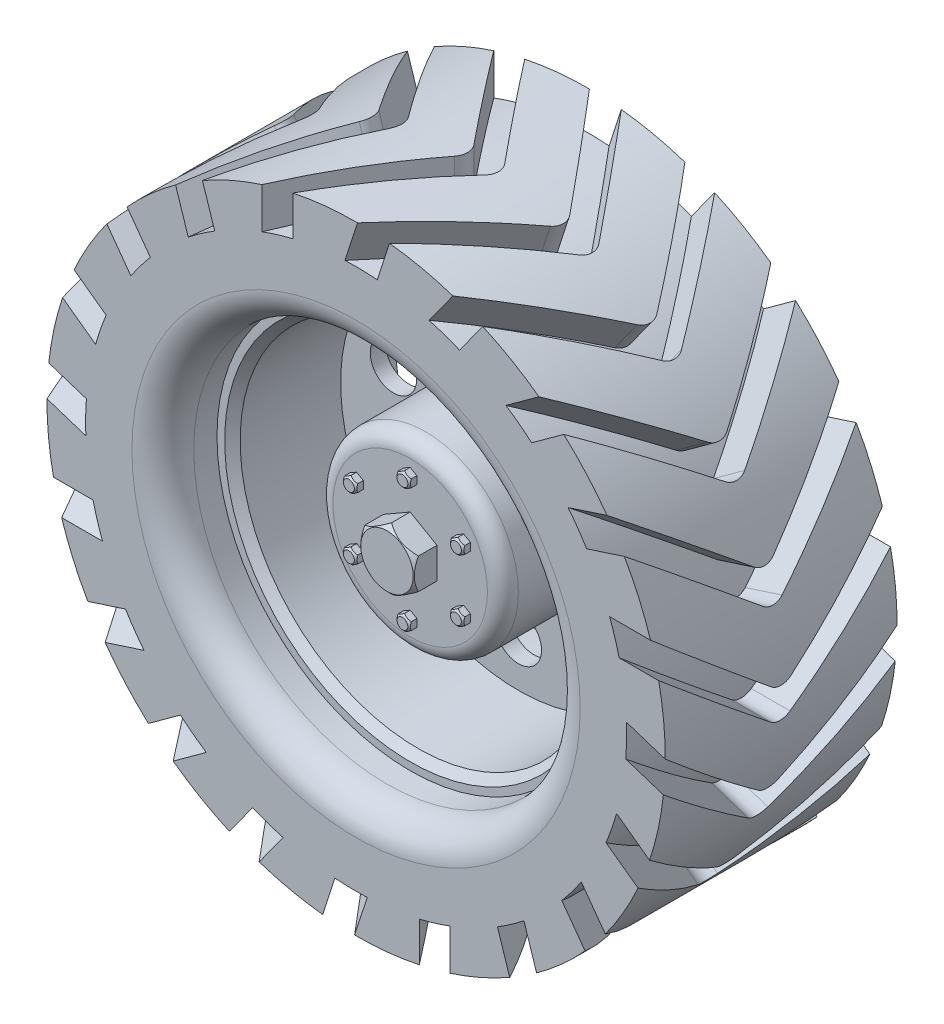
SolidWorks part; units mm, degrees
ref_plane "前基準面" through (0, 0, 0) normal (0, 0, 1) x (1, 0, 0)
ref_plane "上基準面" through (0, 0, 0) normal (0, 1, 0) x (1, 0, 0)
ref_plane "右基準面" through (0, 0, 0) normal (1, 0, 0) x (0, 0, -1)
sketch "草圖1" plane through (0, 0, 0) normal (0, 0, 1) x (1, 0, 0)
  circle A0 centre (0, 0) radius 125
  dimension "D1" = 250
extrude "填料-伸長1" add sketch "草圖1" along normal mid plane 80
shell "薄殼1" thickness 10
sketch "草圖3" plane through (0, 0, 0) normal (0, 0, 1) x (1, 0, 0)
  circle A0 centre (0, 0) radius 200
  circle A1 centre (0, 0) radius 125
  dimension "D1" = 400
  dimension "D2" = 250
extrude "填料-伸長2" add sketch "草圖3" along normal mid plane 150
chamfer "導角1" distance 5 angle 45 1 edges at (115, 0, 40)
fillet "圓角2" radius 20 1 edges at (125, 0, 75)
sketch "草圖4" plane through (0, 0, -30) normal (0, 0, 1) x (1, 0, 0)
  circle A0 centre (0, 0) radius 60
  dimension "D1" = 120
extrude "填料-伸長3" add sketch "草圖4" along normal up to surface (70 mm away) up to face at (120, 0, 40)
fillet "圓角4" radius 10 1 edges at (60, 0, 40)
sketch "草圖5" plane through (0, 0, -30) normal (0, 0, 1) x (1, 0, 0)
  line L0 (0, 0) -> (0, 85) construction
  circle A0 centre (0, 85) radius 15
  dimension "D1" = 30
  dimension "D2" = 85
extrude "除料-伸長2" cut sketch "草圖5" against normal blind 100
pattern_circular "環狀複製排列1" count 10 over 360 about axis through (0, 0, 0) along (0, 0, 1) of "除料-伸長2"
fillet "圓角5" radius 5 1 edges at (60, 0, -30)
sketch "草圖7" plane through (0, 0, 40) normal (0, 0, 1) x (1, 0, 0)
  circle A0 centre (0, 0) radius 20
  dimension "D1" = 40
extrude "填料-伸長5" add sketch "草圖7" along normal blind 15
chamfer "導角2" distance 3 angle 45 1 edges at (20, 0, 55)
sketch "草圖8" plane through (0, 0, 55) normal (0, 0, 1) x (1, 0, 0)
  line L1 (0, 20) -> (-17.3205, 10)
  line L2 (-17.3205, 10) -> (-17.3205, -10)
  line L3 (-17.3205, -10) -> (0, -20)
  line L4 (0, -20) -> (17.3205, -10)
  line L5 (17.3205, -10) -> (17.3205, 10)
  line L6 (17.3205, 10) -> (0, 20)
  circle A0 centre (0, 0) radius 17.3205 construction
  circle A1 centre (0, 0) radius 20
extrude "除料-伸長3" cut sketch "草圖8" against normal blind 15 contours L1 A1 | L6 A1 | L2 A1 | L3 A1 | L4 A1 | L5 A1
sketch "草圖9" plane through (0, 0, 40) normal (0, 0, 1) x (1, 0, 0)
  circle A0 centre (0, 0) radius 40 construction
  circle A1 centre (0, 40) radius 5
  dimension "D1" = 80
  dimension "D2" = 10
extrude "填料-伸長6" add sketch "草圖9" along normal blind 5
chamfer "導角3" distance 1.5 angle 45 1 edges at (5, 40, 45)
pattern_circular "環狀複製排列2" count 6 over 360 about axis through (0, 0, 0) along (0, 0, 1) of "填料-伸長6"
chamfer "導角4" distance 1.5 angle 45 5 edges at (37.141, 15.6699, 45) (32.141, -24.3301, 45) (-5, -40, 45) (-37.141, -15.6699, 45) (-32.141, 24.3301, 45)
sketch "草圖10" plane through (0, 0, 45) normal (0, 0, 1) x (1, 0, 0)
  line L1 (0, 45) -> (-4.3301, 42.5)
  line L2 (-4.3301, 42.5) -> (-4.3301, 37.5)
  line L3 (-4.3301, 37.5) -> (0, 35)
  line L4 (0, 35) -> (4.3301, 37.5)
  line L5 (4.3301, 37.5) -> (4.3301, 42.5)
  line L6 (4.3301, 42.5) -> (0, 45)
  circle A0 centre (0, 40) radius 4.3301 construction
  circle A1 centre (0, 40) radius 5
extrude "除料-伸長4" cut sketch "草圖10" against normal blind 5 contours L1 A1 | L6 A1 | L2 A1 | L3 A1 | L4 A1 | L5 A1
pattern_circular "環狀複製排列4" count 6 over 360 about axis through (0, 0, 0) along (0, 0, 1) of "除料-伸長4"
ref_plane "平面1" through (0, 300, 0) normal (0, 1, 0) x (1, 0, 0)
sketch "草圖11" plane through (0, 300, 0) normal (0, 1, 0) x (1, 0, 0)
  line L1 (-5.1172, -6.303) -> (-60.8905, -75)
  line L2 (0, 0) -> (20, 0) construction
  line L8 (-200, -75) -> (200, -75) construction
  line L9 (-5.1172, 6.303) -> (-60.8905, 75)
  line L10 (200, 75) -> (-200, 75) construction
  line L11 (-60.8905, 75) -> (-60.8905, -75) construction
  line L16 (14.8828, -6.303) -> (-40.8905, -75)
  line L17 (14.8828, 6.303) -> (-40.8905, 75)
  line L18 (-60.8905, -75) -> (-40.8905, -75)
  line L19 (-60.8905, 75) -> (-40.8905, 75)
  arc A0 (14.8828, -6.303) -> (14.8828, 6.303) centre (7.1192, 0) ccw
  arc A1 (-5.1172, -6.303) -> (-5.1172, 6.303) centre (-12.8808, 0) ccw
  dimension "D2" = 10
  dimension "D1" = 20
sketch "草圖13" plane through (0, 0, 75) normal (0, 0, 1) x (1, 0, 0)
  circle A0 centre (0, 0) radius 175
  dimension "D1" = 350
surface "曲面-伸長1" sketch "草圖13" parameters "D1"=176
extrude "除料-伸長5" cut sketch "草圖11" against normal up to surface (125.0748 mm away)
pattern_circular "環狀複製排列6" count 20 over 360 about axis through (0, 0, 0) along (0, 0, 1) of "除料-伸長5"
sketch "草圖14" plane through (0, 0, -40) normal (0, 0, -1) x (-1, 0, 0)
  circle A0 centre (0, 0) radius 25
  dimension "D1" = 50
extrude "填料-伸長7" add sketch "草圖14" along normal blind 80
